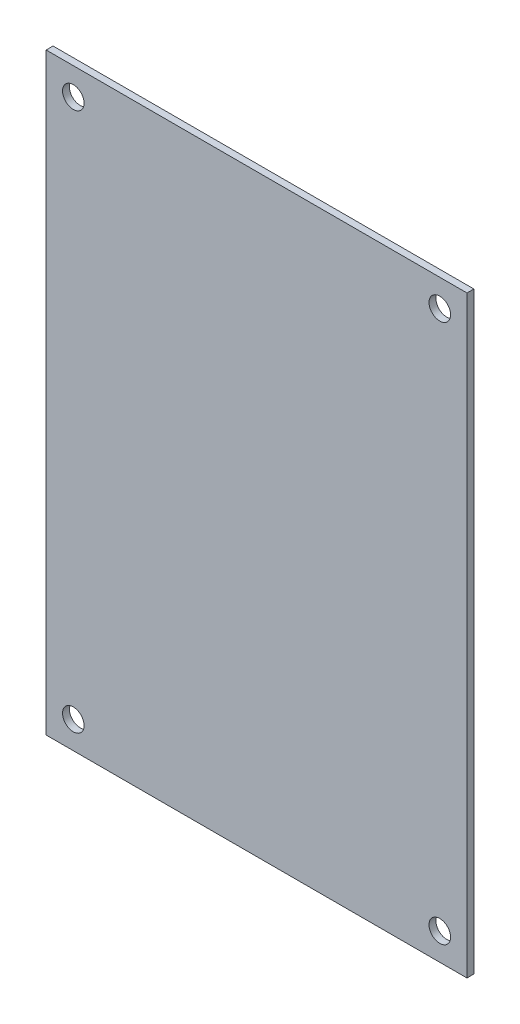
SolidWorks part; units mm, degrees
ref_plane "Front Plane" through (0, 0, 0) normal (0, 0, 1) x (1, 0, 0)
ref_plane "Top Plane" through (0, 0, 0) normal (0, 1, 0) x (1, 0, 0)
ref_plane "Right Plane" through (0, 0, 0) normal (1, 0, 0) x (0, 0, -1)
sketch "Sketch1" plane through (0, 0, 0) normal (0, 0, 1) x (1, 0, 0)
  line L1 (-61.976, -87.376) -> (61.976, -87.376)
  line L2 (-61.976, -87.376) -> (-61.976, 87.376)
  line L3 (-61.976, 87.376) -> (61.976, 87.376)
  line L4 (61.976, -87.376) -> (61.976, 87.376)
  line L5 (-61.976, -87.376) -> (61.976, 87.376) construction
  line L6 (-61.976, 87.376) -> (61.976, -87.376) construction
  line L9 (0, 0) -> (-61.976, 0) construction
  line L10 (0, 0) -> (0, -87.376) construction
  circle A2 centre (-53.975, -79.375) radius 3.175
  circle A9 centre (-53.975, 79.375) radius 3.175
  circle A10 centre (53.975, -79.375) radius 3.175
  circle A11 centre (53.975, 79.375) radius 3.175
  point P0 (0, 0)
  dimension "Mounting Hole Diameter" = 6.35
  dimension "D2" = 8.001
  dimension "D1" = 8.001
  dimension "Height" = 174.752
  dimension "Width" = 123.952
  dimension "Mounting Hole Center to Center Width" = 107.95
  dimension "Mounting Hole Center to Center Height" = 158.75
sketch "Sketch2" plane through (0, 0, 0) normal (1, 0, 0) x (0, 0, -1)
  line L0 (-1.016, 0) -> (1.016, 0) construction
  point P4 (0, 0)
  dimension "Thickness" = 2.032
sketch "Sketch3" plane through (0, 0, 0) normal (0, 0, 1) x (1, 0, 0)
  line L1 (-61.976, -87.376) -> (61.976, -87.376)
  line L2 (-61.976, -87.376) -> (-61.976, 87.376)
  line L3 (-61.976, 87.376) -> (61.976, 87.376)
  line L4 (61.976, -87.376) -> (61.976, 87.376)
  line L5 (-61.976, -87.376) -> (61.976, 87.376) construction
  line L6 (-61.976, 87.376) -> (61.976, -87.376) construction
  circle A0 centre (-53.975, -79.375) radius 3.175 construction
  circle A1 centre (-53.975, 79.375) radius 3.175 construction
  circle A2 centre (-53.975, 79.375) radius 3.175
  circle A3 centre (53.975, 79.375) radius 3.175 construction
  circle A4 centre (53.975, 79.375) radius 3.175
  circle A5 centre (-53.975, -79.375) radius 3.175
  circle A6 centre (53.975, -79.375) radius 3.175 construction
  circle A15 centre (53.975, -79.375) radius 3.175
  point P0 (0, 0)
extrude "Boss-Extrude1" add sketch "Sketch3" against normal up to vertex (1.016 mm away) and the other way up to vertex (1.016 mm away) up to point (0, 0, -1.016) other way up to point (0, 0, 1.016)
